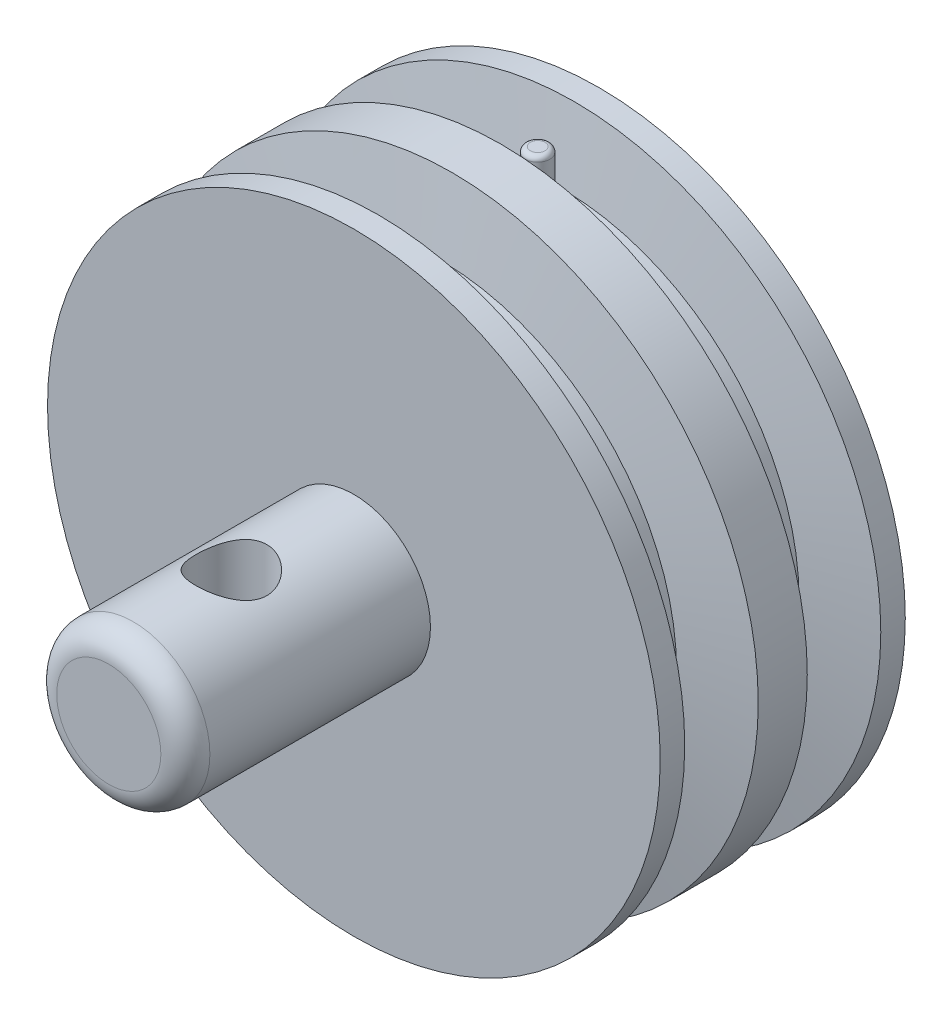
SolidWorks part; units mm, degrees
ref_plane "Plan de face" through (0, 0, 0) normal (0, 0, 1) x (1, 0, 0)
ref_plane "Plan de dessus" through (0, 0, 0) normal (0, 1, 0) x (1, 0, 0)
ref_plane "Plan de droite" through (0, 0, 0) normal (1, 0, 0) x (0, 0, -1)
sketch "Esquisse1" plane through (0, 0, 0) normal (0, 0, 1) x (1, 0, 0)
  circle A0 centre (0, 0) radius 3.125
  dimension "D1" = 6.25
extrude "Boss.-Extru.1" add sketch "Esquisse1" along normal blind 10
fillet "Congé1" radius 1 1 edges at (3.125, 0, 10)
sketch "Esquisse2" plane through (0, 0, 0) normal (0, 0, -1) x (-1, 0, 0)
  circle A0 centre (0, 0) radius 12.5
  dimension "D1" = 25
extrude "Boss.-Extru.3" add sketch "Esquisse2" along normal blind 10
sketch "Esquisse5" plane through (0, 0, 0) normal (1, 0, 0) x (0, 0, -1)
  line L0 (1, 12.5) -> (1.5, 9.6644)
  line L1 (10, 12.5) -> (0, 12.5) construction
  line L2 (1.5, 9.6644) -> (3.5, 9.6644)
  line L3 (3.5, 9.6644) -> (4, 12.5)
  line L4 (4, 12.5) -> (1, 12.5)
  line L5 (0, 0) -> (10, 0) construction
  line L6 (10, -12.5) -> (10, 12.5) construction
  line L7 (5, 0) -> (5, 12.5) construction
  line L8 (0, 12.5) -> (1, 12.5) construction
  line L9 (4, 12.5) -> (5, 12.5) construction
  line L10 (6, 12.5) -> (9, 12.5)
  line L11 (6.5, 9.6644) -> (6, 12.5)
  line L12 (9, 12.5) -> (8.5, 9.6644)
  line L13 (8.5, 9.6644) -> (6.5, 9.6644)
  point P14 (0.5691, 7.499)
  dimension "D1" = 20
  dimension "D2" = 2
  dimension "D3" = 3
revolve "Enlèvement de matière-Révolution1" cut sketch "Esquisse5" angle 360 about L5
sketch "Esquisse6" plane through (0, 0, 0) normal (0, 1, 0) x (1, 0, 0)
  line L0 (0, 0) -> (0, -10) construction
  line L1 (-2.125, -10) -> (2.125, -10) construction
  circle A0 centre (0, -5) radius 1.45
  point P7 (0, -5)
  dimension "D1" = 2.9
extrude "Enlèv. mat.-Extru.1" cut sketch "Esquisse6" against normal through all both and the other way through all
ref_plane "Plan1" through (0, 9.6644, 0) normal (0, 1, 0) x (1, 0, 0)
sketch "Esquisse7" plane through (0, 9.6644, 0) normal (0, 1, 0) x (1, 0, 0)
  line L0 (0, 7.5) -> (0, 0) construction
  line L1 (-1.2647, 6.5) -> (-1.2647, 8.5) construction
  line L2 (9.6644, 6.5) -> (-9.6644, 6.5) construction
  line L3 (9.6644, 8.5) -> (-9.6644, 8.5) construction
  circle A0 centre (0, 7.5) radius 0.5
  point P10 (-1.2647, 7.5)
  dimension "D1" = 1
extrude "Boss.-Extru.4" add sketch "Esquisse7" along normal blind 2 and the other way blind 1
ref_plane "Plan2" through (0, -9.6644, 0) normal (0, -1, 0) x (-1, 0, 0)
sketch "Esquisse8" plane through (0, -9.6644, 0) normal (0, -1, 0) x (-1, 0, 0)
  line L0 (0, 0) -> (0, 2.5) construction
  line L1 (3.0489, 3.5) -> (3.0489, 1.5) construction
  line L2 (-9.6644, 3.5) -> (9.6644, 3.5) construction
  line L3 (-9.6644, 1.5) -> (9.6644, 1.5) construction
  circle A0 centre (0, 2.5) radius 0.5
  point P10 (3.0489, 2.5)
  dimension "D1" = 1
extrude "Boss.-Extru.5" add sketch "Esquisse8" along normal blind 2 and the other way blind 1
fillet "Congé2" radius 0.2 2 edges at (0, 11.6644, -7) (0, -11.6644, -3)
